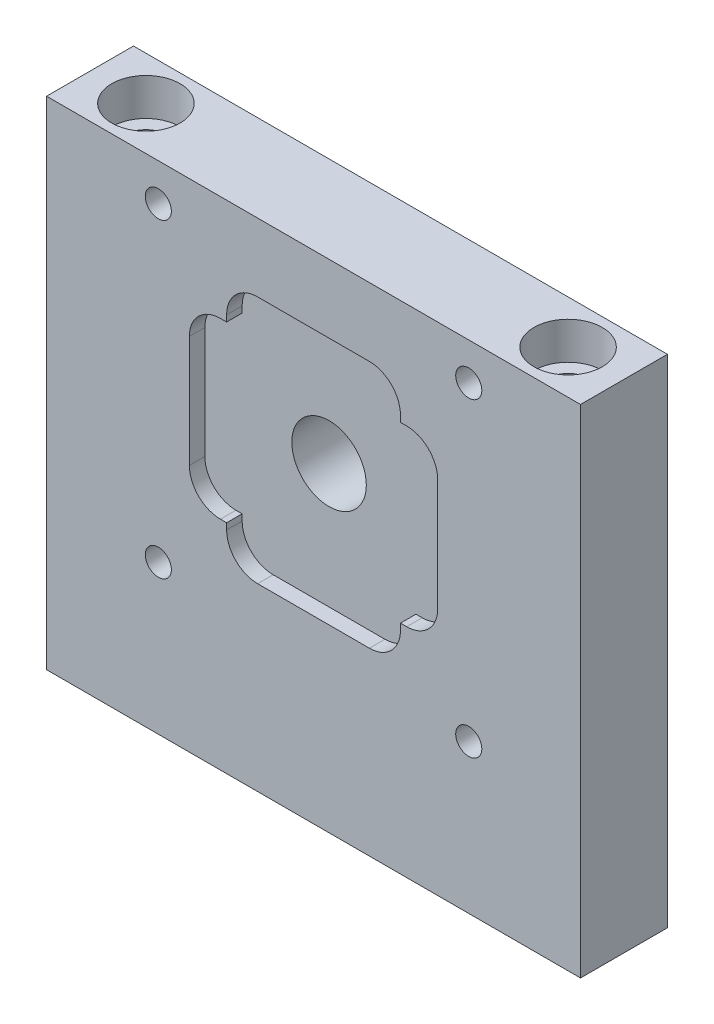
SolidWorks part; units mm, degrees
material "SKD11淬火HRC56-60"
ref_plane "前基準面" through (0, 0, 0) normal (0, 0, 1) x (1, 0, 0)
ref_plane "上基準面" through (0, 0, 0) normal (0, 1, 0) x (1, 0, 0)
ref_plane "右基準面" through (0, 0, 0) normal (1, 0, 0) x (0, 0, -1)
sketch "草图1" plane through (0, 0, 0) normal (0, 0, 1) x (1, 0, 0)
  line L1 (0, 0) -> (86, 0)
  line L2 (0, 0) -> (0, 80)
  line L3 (0, 80) -> (86, 80)
  line L4 (86, 0) -> (86, 80)
  dimension "D1" = 86
  dimension "D2" = 80
extrude "凸台-拉伸1" add sketch "草图1" along normal blind 14
sketch "草图2" plane through (0, 0, 14) normal (0, 0, 1) x (1, 0, 0)
  line L0 (43, 80) -> (43, 0) construction
  line L1 (86, 80) -> (0, 80) construction
  line L2 (0, 0) -> (86, 0) construction
  circle A0 centre (43, 49) radius 6
  dimension "D1" = 12
  dimension "D2" = 49
extrude "切除-拉伸1" cut sketch "草图2" against normal through all
sketch "草图3" plane through (0, 0, 14) normal (0, 0, 1) x (1, 0, 0)
  line L0 (43, 80) -> (43, 49) construction
  line L1 (86, 80) -> (0, 80) construction
  line L2 (43, 49) -> (0, 49) construction
  line L3 (0, 80) -> (0, 0) construction
  line L4 (57, 69) -> (29, 69)
  line L5 (29, 69) -> (29, 63)
  line L6 (29, 63) -> (23, 63)
  line L7 (23, 63) -> (23, 35)
  line L8 (63, 63) -> (63, 35)
  line L9 (57, 63) -> (63, 63)
  line L10 (57, 69) -> (57, 63)
  line L11 (57, 29) -> (57, 35)
  line L12 (57, 35) -> (63, 35)
  line L13 (29, 35) -> (23, 35)
  line L14 (29, 29) -> (29, 35)
  line L15 (57, 29) -> (29, 29)
  point P5 (43, 29)
  point P17 (43, 69)
  point P21 (63, 49)
  point P22 (23, 49)
  dimension "D1" = 6
  dimension "D2" = 40
extrude "切除-拉伸2" cut sketch "草图3" against normal blind 2.5
fillet "圆角1" radius 5 8 edges at (57, 69, 12.75) (63, 63, 12.75) (63, 35, 12.75) (57, 29, 12.75) (29, 29, 12.75) (23, 35, 12.75) (23, 63, 12.75) (29, 69, 12.75)
hole_wizard "M6 六角凹头螺钉的柱形沉头孔1" positions "草图5" profile "草图4" counterbore size "M6" standard "ISO" end condition through all
sketch "草图5" plane through (0, 80, 0) normal (0, 1, 0) x (-1, 0, 0)
  line L0 (-86, 7) -> (0, 7) construction
  line L1 (-86, 14) -> (-86, 0) construction
  line L2 (0, 14) -> (0, 0) construction
  line L3 (-43, 0) -> (-43, 14) construction
  line L4 (-86, 0) -> (0, 0) construction
  line L5 (-86, 14) -> (0, 14) construction
  point P0 (-9, 7)
  point P1 (-77, 7)
  dimension "D1" = 68
sketch "草图4" plane through (9, 80, 7) normal (1, 0, 0) x (0, 0, 1)
  line L0 (0, 0) -> (0, 80)
  line L1 (0, 80) -> (3.3, 80)
  line L3 (3.3, 80) -> (3.3, 6)
  line L4 (3.3, 6) -> (5.5, 6)
  line L5 (5.5, 6) -> (5.5, 0)
  line L7 (5.5, 0) -> (0, 0)
  line L11 (0, -6.35) -> (0, 107.95) construction
  dimension "通孔孔直径" = 6.6
  dimension "通孔孔深度" = 80
  dimension "柱形沉头孔直径" = 11
  dimension "柱形沉头孔深度" = 6
hole_wizard "M5 螺纹孔1" positions "草图7" profile "草图8" tap size "M5" standard "ISO" end condition through all
sketch "草图7" plane through (0, 0, 14) normal (0, 0, 1) x (1, 0, 0)
  point P0 (68, 74)
  point P1 (18, 74)
  point P4 (18, 24)
  point P7 (68, 24)
sketch "草图8" plane through (68, 74, 14) normal (1, 0, 0) x (0, -1, 0)
  line L0 (0, 0) -> (0, 14)
  line L1 (0, 14) -> (2.1, 14)
  line L2 (2.1, 14) -> (2.1, 0)
  line L5 (2.1, 0) -> (0, 0)
  line L11 (0, -6.35) -> (0, 107.95) construction
  dimension "通孔螺纹孔钻头直径" = 4.2
  dimension "通孔螺纹孔钻头深度" = 14
cosmetic thread "孔螺蚊线1" parameters "D2"=5
cosmetic thread "孔螺蚊线2" parameters "D2"=5
cosmetic thread "孔螺蚊线3" parameters "D2"=5
cosmetic thread "孔螺蚊线4" parameters "D2"=5
